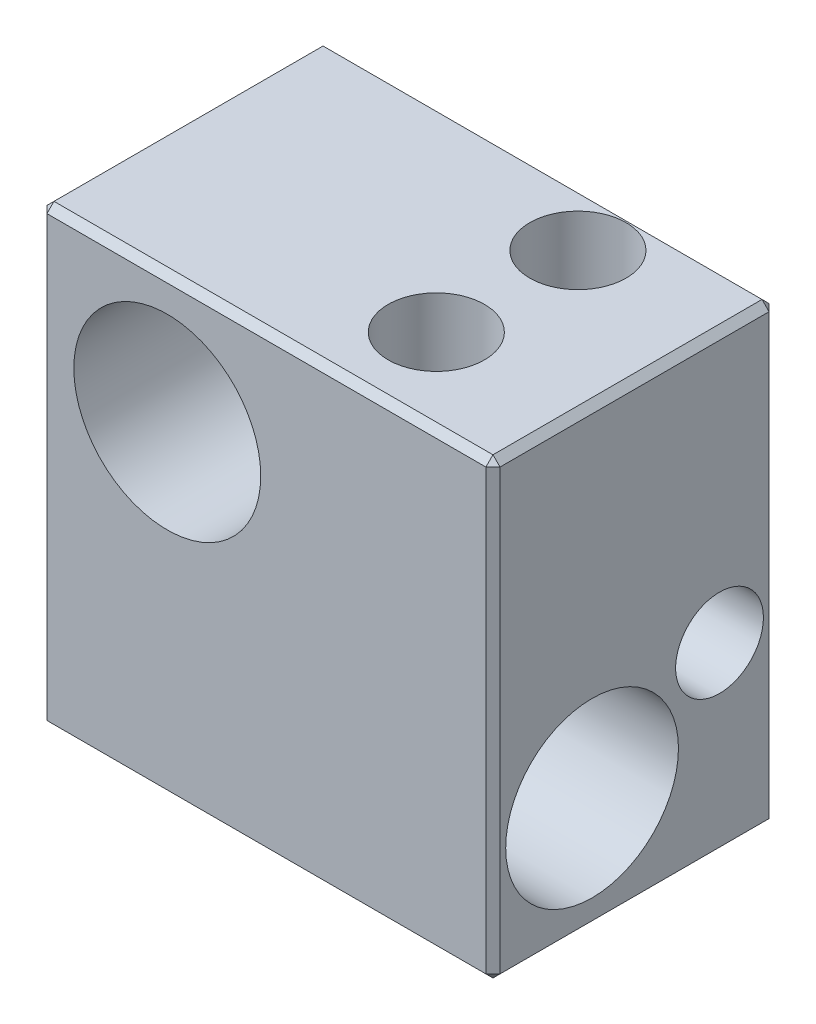
SolidWorks part; units mm, degrees
ref_plane "Plan de face" through (0, 0, 0) normal (0, 0, 1) x (1, 0, 0)
ref_plane "Plan de dessus" through (0, 0, 0) normal (0, 1, 0) x (1, 0, 0)
ref_plane "Plan de droite" through (0, 0, 0) normal (1, 0, 0) x (0, 0, -1)
sketch "Esquisse1" plane through (0, 0, 0) normal (0, 0, 1) x (1, 0, 0)
  line L1 (0, 0) -> (16, 0)
  line L2 (0, 0) -> (0, 16)
  line L3 (0, 16) -> (16, 16)
  line L4 (16, 0) -> (16, 16)
  dimension "D1" = 16
  dimension "D2" = 16
extrude "Boss.-Extru.1" add sketch "Esquisse1" along normal blind 10
sketch "Esquisse2" plane through (0, 0, 10) normal (0, 0, 1) x (1, 0, 0)
  line L0 (16, 16) -> (0, 16) construction
  line L1 (0, 16) -> (0, 0) construction
  circle A0 centre (4.5, 11.5) radius 3
  dimension "D1" = 6
  dimension "D2" = 4.5
  dimension "D3" = 4.5
hole_wizard "Dégagement M61" positions "Esquisse4" profile "Esquisse3" hole size "M6" standard "ISO" end condition through all
sketch "Esquisse4" plane through (0, 0, 10) normal (0, 0, 1) x (1, 0, 0)
  point P0 (4.5, 11.5)
sketch "Esquisse3" plane through (4.5, 11.5, 10) normal (1, 0, 0) x (0, -1, 0)
  line L0 (0, 0) -> (0, 10)
  line L1 (0, 10) -> (3.3, 10)
  line L2 (3.3, 10) -> (3.3, 0)
  line L5 (3.3, 0) -> (0, 0)
  line L11 (0, -6.35) -> (0, 107.95) construction
  dimension "Diamètre du perçage jusqu'au prochain" = 6.6
  dimension "Profondeur du perçage jusqu'au prochain" = 10
sketch "Esquisse5" plane through (16, 0, 0) normal (1, 0, 0) x (0, 0, -1)
  line L0 (-10, 0) -> (-10, 16) construction
  line L1 (-10, 0) -> (0, 0) construction
  line L2 (0, 0) -> (0, 16) construction
  circle A0 centre (-6.5, 4) radius 3
  circle A1 centre (-2, 6.5) radius 1.5
  dimension "D3" = 6
  dimension "D6" = 3
  dimension "D1" = 3.5
  dimension "D2" = 4
  dimension "D4" = 6.5
  dimension "D5" = 2
hole_wizard "Diamètre du perçage Ø6.1 (6.1)1" positions "Esquisse7" profile "Esquisse6" hole size "Ø6.1" standard "ISO" end condition through all
sketch "Esquisse7" plane through (16, 0, 0) normal (1, 0, 0) x (0, 0, -1)
  point P0 (-6.5, 4)
sketch "Esquisse6" plane through (16, 4, 6.5) normal (0, 1, 0) x (0, 0, -1)
  line L0 (0, 0) -> (0, 16)
  line L1 (0, 16) -> (3.05, 16)
  line L2 (3.05, 16) -> (3.05, 0)
  line L5 (3.05, 0) -> (0, 0)
  line L11 (0, -6.35) -> (0, 107.95) construction
  dimension "Diamètre du perçage jusqu'au prochain" = 6.1
  dimension "Profondeur du perçage jusqu'au prochain" = 16
hole_wizard "Diamètre du perçage Ø3.1 (3.1)1" positions "Esquisse9" profile "Esquisse8" hole size "Ø3.1" standard "ISO" end condition through all
sketch "Esquisse9" plane through (16, 0, 0) normal (1, 0, 0) x (0, 0, -1)
  point P0 (-2, 6.5)
sketch "Esquisse8" plane through (16, 6.5, 2) normal (0, 1, 0) x (0, 0, -1)
  line L0 (0, 0) -> (0, 16)
  line L1 (0, 16) -> (1.55, 16)
  line L2 (1.55, 16) -> (1.55, 0)
  line L5 (1.55, 0) -> (0, 0)
  line L11 (0, -6.35) -> (0, 107.95) construction
  dimension "Diamètre du perçage jusqu'au prochain" = 3.1
  dimension "Profondeur du perçage jusqu'au prochain" = 16
sketch "Esquisse10" plane through (0, 16, 0) normal (0, 1, 0) x (1, 0, 0)
  line L1 (16, -10) -> (16, 0) construction
  line L2 (16, 0) -> (0, 0) construction
  line L3 (16, -10) -> (0, -10) construction
  circle A0 centre (11, -2) radius 1.5
  circle A1 centre (11, -7) radius 1.5
  dimension "D1" = 3
  dimension "D2" = 3
  dimension "D3" = 5
  dimension "D4" = 5
  dimension "D5" = 2
  dimension "D6" = 3
hole_wizard "Dégagement M31" positions "Esquisse12" profile "Esquisse11" hole size "M3" standard "ISO"
sketch "Esquisse12" plane through (0, 16, 0) normal (0, 1, 0) x (1, 0, 0)
  point P0 (11, -7)
sketch "Esquisse11" plane through (11, 16, 7) normal (1, 0, 0) x (0, 0, 1)
  line L0 (0, 0) -> (0, 12.0215)
  line L1 (0, 12.0215) -> (1.7, 11)
  line L2 (1.7, 11) -> (1.7, 0)
  line L5 (1.7, 0) -> (0, 0)
  line L10 (0, 12.0215) -> (-1.7, 11) construction
  line L11 (0, -6.35) -> (0, 107.95) construction
  dimension "Diamètre du perçage" = 3.4
  dimension "Profondeur du perçage" = 11
  dimension "Angle de pointe" = 118
hole_wizard "Dégagement M33" positions "Esquisse16" profile "Esquisse15" hole size "M3" standard "ISO"
sketch "Esquisse16" plane through (0, 16, 0) normal (0, 1, 0) x (1, 0, 0)
  point P0 (11, -2)
sketch "Esquisse15" plane through (11, 16, 2) normal (1, 0, 0) x (0, 0, 1)
  line L0 (0, 0) -> (0, 10.5215)
  line L1 (0, 10.5215) -> (1.7, 9.5)
  line L2 (1.7, 9.5) -> (1.7, 0)
  line L5 (1.7, 0) -> (0, 0)
  line L10 (0, 10.5215) -> (-1.7, 9.5) construction
  line L11 (0, -6.35) -> (0, 107.95) construction
  dimension "Diamètre du perçage" = 3.4
  dimension "Profondeur du perçage" = 9.5
  dimension "Angle de pointe" = 118
chamfer "Chanfrein1" distance 0.25 angle 45 12 edges at (8, 0, 0) (0, 0, 5) (0, 8, 0) (0, 16, 5) (8, 16, 0) (16, 0, 5) (16, 8, 0) (16, 16, 5) (16, 8, 10) (8, 16, 10) (0, 8, 10) (8, 0, 10)
